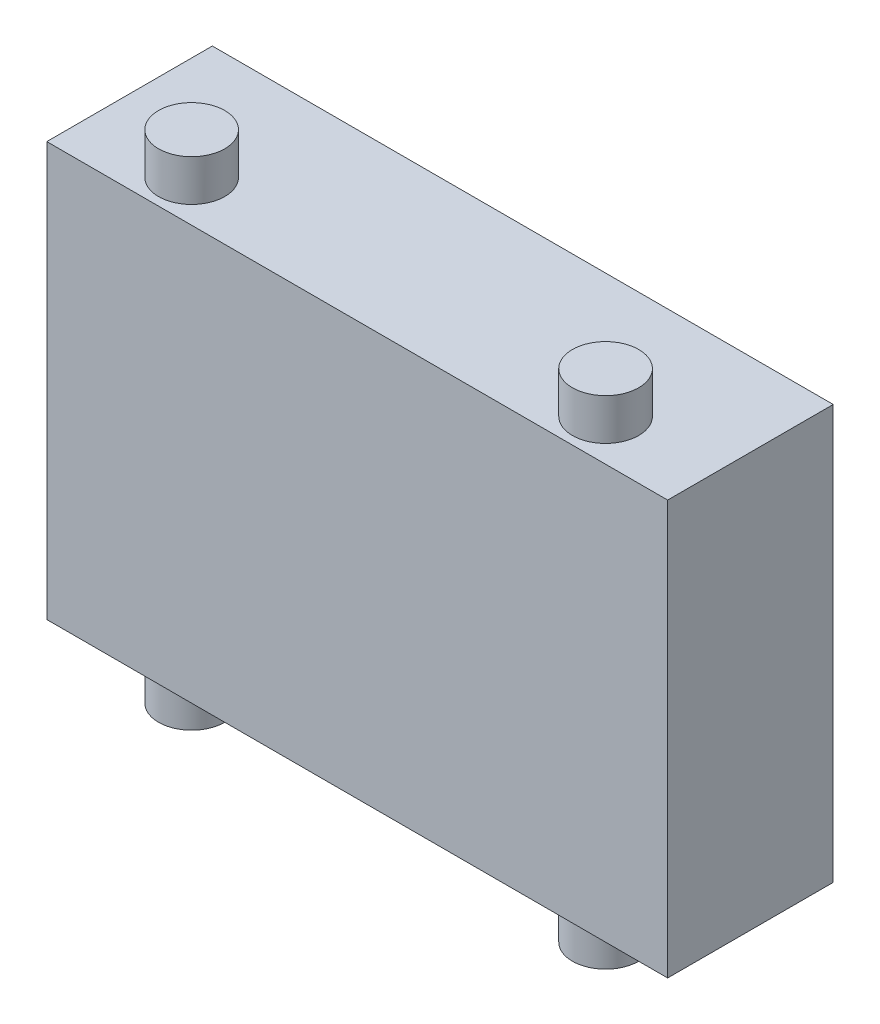
SolidWorks part; units mm, degrees
ref_plane "前视基准面" through (0, 0, 0) normal (0, 0, 1) x (1, 0, 0)
ref_plane "上视基准面" through (0, 0, 0) normal (0, 1, 0) x (1, 0, 0)
ref_plane "右视基准面" through (0, 0, 0) normal (1, 0, 0) x (0, 0, -1)
sketch "草图1" plane through (0, 0, 0) normal (0, 0, 1) x (1, 0, 0)
  line L1 (-150, -100) -> (150, -100)
  line L2 (-150, -100) -> (-150, 100)
  line L3 (-150, 100) -> (150, 100)
  line L4 (150, -100) -> (150, 100)
  line L5 (-150, -100) -> (150, 100) construction
  line L6 (-150, 100) -> (150, -100) construction
  point P0 (0, 0)
  dimension "D1" = 300
  dimension "D2" = 200
extrude "凸台-拉伸1" add sketch "草图1" along normal blind 80
sketch "草图2" plane through (0, 100, 0) normal (0, 1, 0) x (1, 0, 0)
  line L0 (-174.2297, -60) -> (178.9386, -60) construction
  line L1 (0, 0) -> (0, -80) construction
  line L2 (150, 0) -> (-150, 0) construction
  line L3 (150, -80) -> (-150, -80) construction
  circle A0 centre (-100, -60) radius 16.0115
  circle A1 centre (100, -60) radius 16.0115
  dimension "D1" = 20
  dimension "D2" = 100
extrude "凸台-拉伸2" add sketch "草图2" along normal blind 20
ref_plane "基准面4" through (0, 0, 0) normal (0, 1, 0) x (1, 0, 0)
mirror "镜向1" about plane through (0, 0, 0) normal (0, 1, 0) of "凸台-拉伸2"
sketch "草图3" plane through (0, 0, 0) normal (0, 0, -1) x (-1, 0, 0)
  line L0 (44, 0) -> (-44, 0) construction
  circle A0 centre (84.1101, 0) radius 19.3437
extrude "凸台-拉伸3" add sketch "草图3" along normal blind 20
